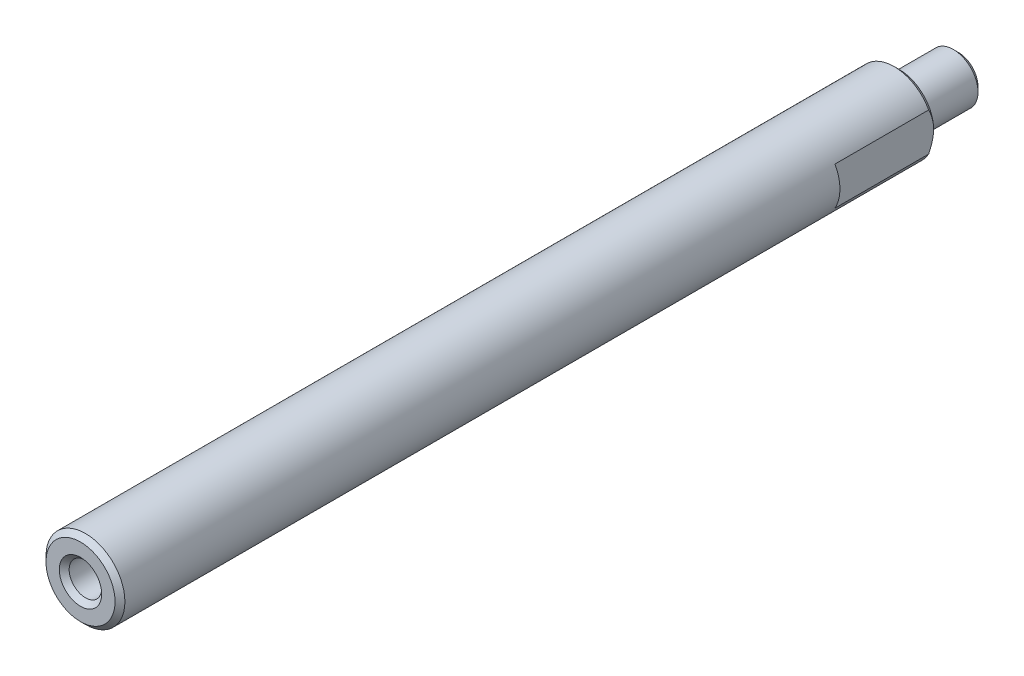
SolidWorks part; units mm, degrees
material "2A12"
ref_plane "前视基准面" through (0, 0, 0) normal (0, 0, 1) x (1, 0, 0)
ref_plane "上视基准面" through (0, 0, 0) normal (0, 1, 0) x (1, 0, 0)
ref_plane "右视基准面" through (0, 0, 0) normal (1, 0, 0) x (0, 0, -1)
sketch "草图1" plane through (0, 0, 0) normal (0, 0, 1) x (1, 0, 0)
  circle A0 centre (0, 0) radius 4
  dimension "D1" = 8
extrude "拉伸1" add sketch "草图1" along normal mid plane 83
hole_wizard "M4 螺纹孔1" positions "3D草图1" profile "草图2" tap size "M4" standard "GB"
sketch3d "3D草图1"
  line L0 (0, 0, 41.5) -> (0, 0, -41.5) construction
  circle A0 centre (0, 0, 41.5) radius 4 construction
  point P0 (0, 0, 41.5)
  point P2 (0, 0, -41.5)
  point P10 (0, 0, 45.5)
sketch "草图2" plane through (0, 0, 41.5) normal (1, 0, 0) x (0, -1, 0)
  line L0 (0, 0) -> (0, 13.0914)
  line L1 (0, 13.0914) -> (1.65, 12.1)
  line L2 (1.65, 12.1) -> (1.65, 0)
  line L5 (1.65, 0) -> (0, 0)
  line L10 (0, 13.0914) -> (-1.65, 12.1) construction
  line L11 (0, -6.35) -> (0, 107.95) construction
  dimension "螺纹孔钻头直径" = 3.3
  dimension "螺纹孔钻头深度" = 12.1
  dimension "导头角度" = 118
cosmetic thread "孔螺蚊线1" parameters "D1"=10, "D2"=4
cosmetic thread "孔螺蚊线2" parameters "D1"=10, "D2"=4
chamfer "倒角1" distance 0.5 angle 45 4 edges at (4, 0, -41.5) (-1.65, 0, -41.5) (4, 0, 41.5) (1.65, 0, 41.5)
sketch "草图3" plane through (0, 0, -41.5) normal (0, 0, -1) x (-1, 0, 0)
  circle A0 centre (0, 0) radius 2.5
  dimension "D1" = 5
extrude "凸台-拉伸1" add sketch "草图3" along normal blind 6
cosmetic thread "装饰螺纹线1" parameters "D2"=4.134
chamfer "倒角2" distance 0.5 angle 45 1 edges at (-2.5, 0, -47.5)
sketch "草图4" plane through (0, 0, -41.5) normal (0, 0, -1) x (-1, 0, 0)
  line L1 (3.5, -5.1785) -> (-3.5, -5.1785)
  line L2 (3.5, -5.1785) -> (3.5, 5.1785)
  line L3 (3.5, 5.1785) -> (-3.5, 5.1785)
  line L4 (-3.5, -5.1785) -> (-3.5, 5.1785)
  line L5 (3.5, -5.1785) -> (-3.5, 5.1785) construction
  line L6 (3.5, 5.1785) -> (-3.5, -5.1785) construction
  point P0 (0, 0)
  dimension "D1" = 7
extrude "切除-拉伸1" cut sketch "草图4" against normal blind 10 flip side to cut
